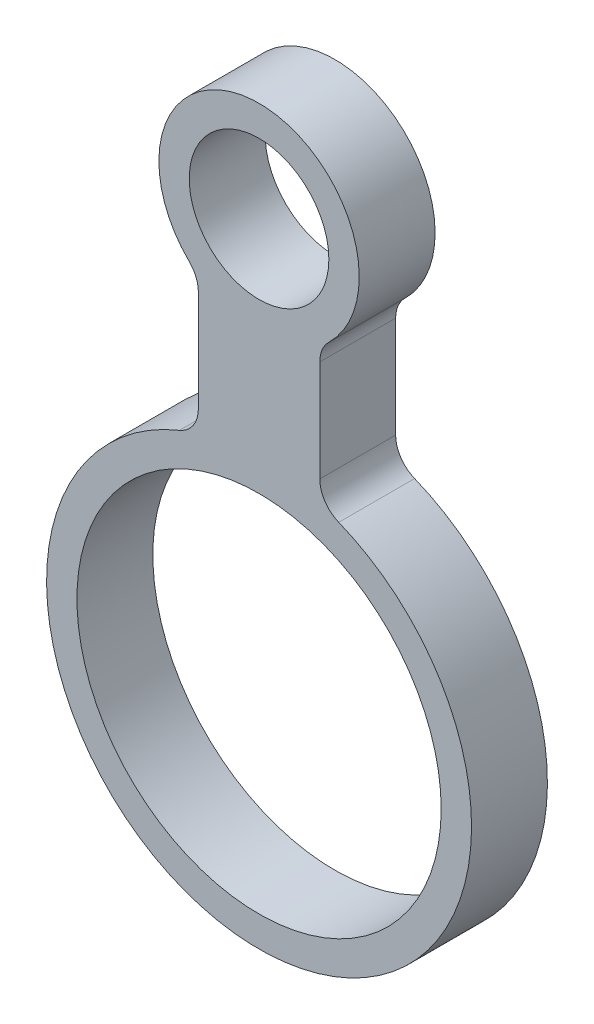
SolidWorks part; units mm, degrees
ref_plane "Front Plane" through (0, 0, 0) normal (0, 0, 1) x (1, 0, 0)
ref_plane "Top Plane" through (0, 0, 0) normal (0, 1, 0) x (1, 0, 0)
ref_plane "Right Plane" through (0, 0, 0) normal (1, 0, 0) x (0, 0, -1)
sketch "Sketch1" plane through (0, 0, 0) normal (0, 0, 1) x (1, 0, 0)
  line L0 (0, 0) -> (0, 92.7368) construction
  line L1 (-4, 22.4164) -> (-4, 13.4164)
  line L2 (4, 22.4164) -> (4, 13.4164)
  line L3 (-4, 22.4164) -> (4, 22.4164) construction
  circle A0 centre (0, 0) radius 12
  arc A1 (-4, 13.4164) -> (4, 13.4164) centre (0, 0) ccw
  arc A3 (4, 22.4164) -> (-4, 22.4164) centre (0, 27.6662) ccw
  circle A4 centre (0, 27.6662) radius 4.6
  circle A5 centre (0, 0) radius 14 construction
  dimension "D1" = 24
  dimension "D5" = 9.2
  dimension "D6" = 2
  dimension "D3" = 9
  dimension "D4" = 4
  dimension "D2" = 2
extrude "Boss-Extrude1" add sketch "Sketch1" along normal blind 5
fillet "Fillet1" radius 2 4 edges at (4, 13.4164, 2.5) (-4, 13.4164, 2.5) (-4, 22.4164, 2.5) (4, 22.4164, 2.5)
